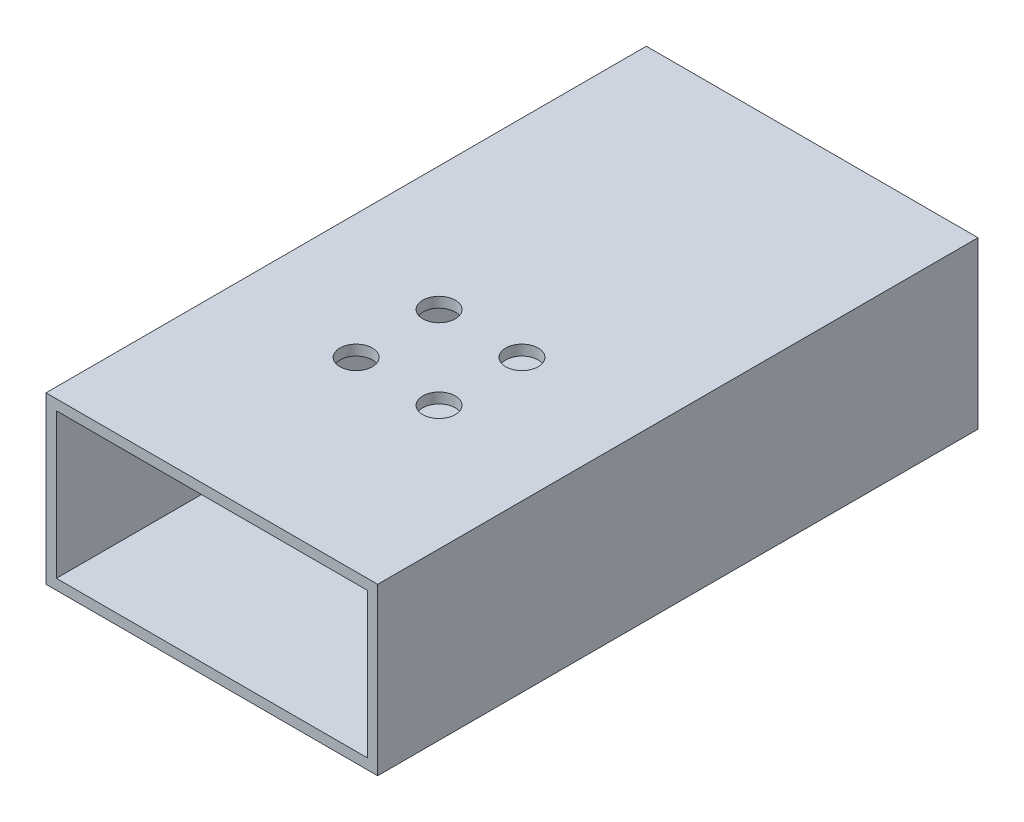
SolidWorks part; units mm, degrees
material "6061-T6 (SS)"
ref_plane "Front Plane" through (0, 0, 0) normal (0, 0, 1) x (1, 0, 0)
ref_plane "Top Plane" through (0, 0, 0) normal (0, 1, 0) x (1, 0, 0)
ref_plane "Right Plane" through (0, 0, 0) normal (1, 0, 0) x (0, 0, -1)
sketch "Sketch1" plane through (0, 0, 0) normal (0, 0, 1) x (1, 0, 0)
  line L1 (-25.4, -12.7) -> (25.4, -12.7)
  line L2 (-25.4, -12.7) -> (-25.4, 12.7)
  line L3 (-25.4, 12.7) -> (25.4, 12.7)
  line L4 (25.4, -12.7) -> (25.4, 12.7)
  line L5 (-25.4, -12.7) -> (25.4, 12.7) construction
  line L6 (-25.4, 12.7) -> (25.4, -12.7) construction
  line L7 (-23.8125, -11.1125) -> (23.8125, -11.1125)
  line L8 (-23.8125, -11.1125) -> (-23.8125, 11.1125)
  line L9 (-23.8125, 11.1125) -> (23.8125, 11.1125)
  line L10 (23.8125, -11.1125) -> (23.8125, 11.1125)
  line L11 (-23.8125, -11.1125) -> (23.8125, 11.1125) construction
  line L12 (-23.8125, 11.1125) -> (23.8125, -11.1125) construction
  point P0 (0, 0)
  point P6 (0, 0)
  dimension "D1" = 50.8
  dimension "D2" = 25.4
  dimension "D3" = 1.5875
  dimension "D4" = 1.5875
extrude "Boss-Extrude1" add sketch "Sketch1" along normal mid plane 91.948
sketch "Sketch2" plane through (0, 12.7, 0) normal (0, 1, 0) x (1, 0, 0)
  line L0 (-6.35, -4.826) -> (6.35, -4.826) construction
  line L2 (25.4, 45.974) -> (-25.4, 45.974) construction
  circle A0 centre (-6.35, -4.826) radius 2.4892
  circle A1 centre (6.35, -4.826) radius 2.4892
  circle A2 centre (-6.35, -17.526) radius 2.4892
  circle A3 centre (6.35, -17.526) radius 2.4892
  point P8 (0, -4.826)
  dimension "D1" = 4.9784
  dimension "D2" = 12.7
  dimension "D3" = 12.7
  dimension "D4" = 50.8
extrude "Cut-Extrude1" cut sketch "Sketch2" against normal through all
